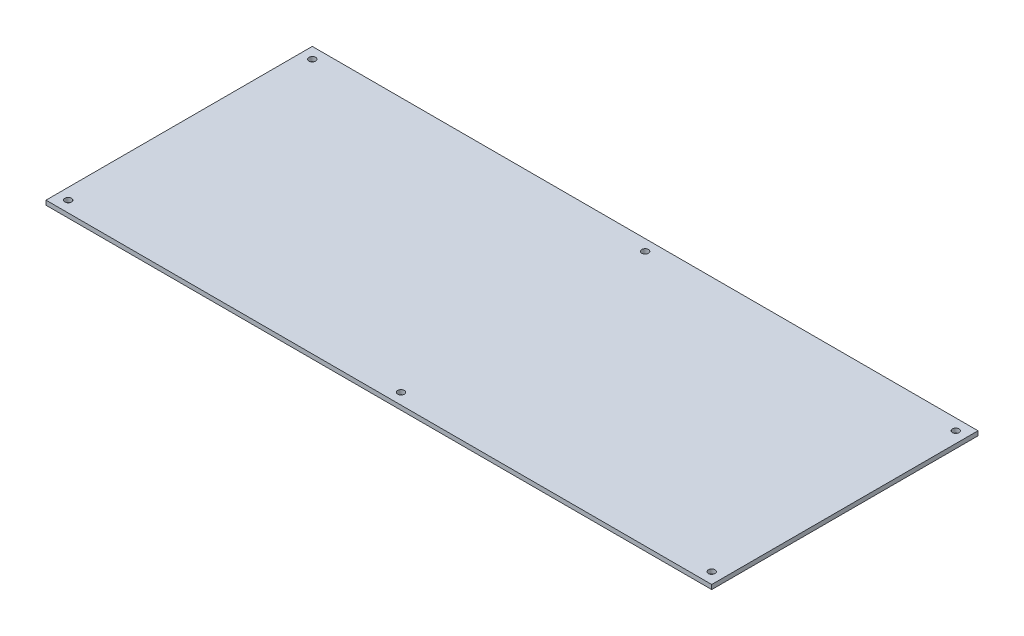
SolidWorks part; units mm, degrees
ref_plane "前视基准面" through (0, 0, 0) normal (0, 0, 1) x (1, 0, 0)
ref_plane "上视基准面" through (0, 0, 0) normal (0, 1, 0) x (1, 0, 0)
ref_plane "右视基准面" through (0, 0, 0) normal (1, 0, 0) x (0, 0, -1)
sketch "Sketch1" plane through (0, 0, 0) normal (0, 1, 0) x (1, 0, 0)
  line L0 (0, 0) -> (0, 75.008) construction
  line L1 (-150, 60) -> (150, 60)
  line L2 (-150, 60) -> (-150, -60)
  line L3 (-150, -60) -> (150, -60)
  line L4 (150, 60) -> (150, -60)
  line L5 (-150, 60) -> (150, -60) construction
  line L6 (-150, -60) -> (150, 60) construction
  line L7 (0, 0) -> (62.2631, 0) construction
  circle A0 centre (-145, 55) radius 1.5
  circle A2 centre (145, 55) radius 1.5
  circle A3 centre (-145, -55) radius 1.5
  circle A4 centre (145, -55) radius 1.5
  circle A5 centre (5, -55) radius 1.5
  circle A6 centre (5, 55) radius 1.5
  point P0 (0, 0)
  dimension "D3" = 3
  dimension "D7" = 140
  dimension "D1" = 300
  dimension "D2" = 120
  dimension "D4" = 5
  dimension "D5" = 5
  dimension "D6" = 2
extrude "Boss-Extrude1" add sketch "Sketch1" along normal blind 2
